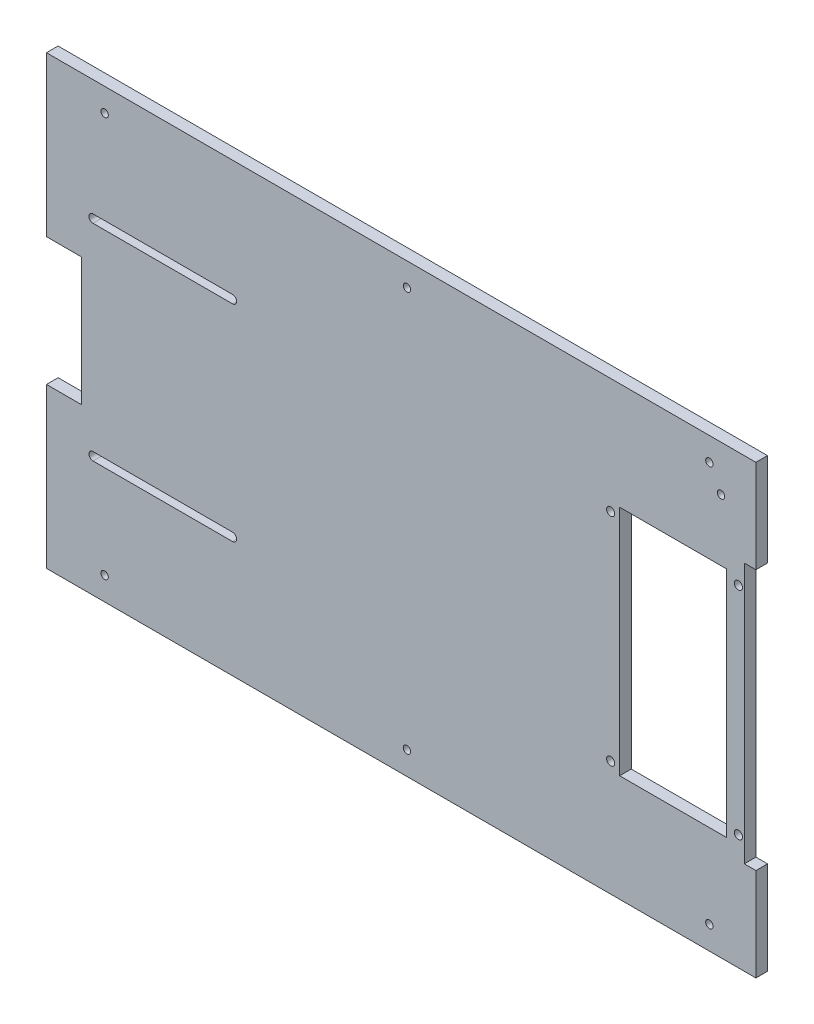
SolidWorks part; units mm, degrees
ref_plane "Front Plane" through (0, 0, 0) normal (0, 0, 1) x (1, 0, 0)
ref_plane "Top Plane" through (0, 0, 0) normal (0, 1, 0) x (1, 0, 0)
ref_plane "Right Plane" through (0, 0, 0) normal (1, 0, 0) x (0, 0, -1)
sketch "Sketch1" plane through (0, 0, 0) normal (0, 0, 1) x (1, 0, 0)
  line L1 (-150, 96) -> (150, 96)
  line L2 (-150, 96) -> (-150, -96)
  line L3 (-150, -96) -> (150, -96)
  line L4 (150, 96) -> (150, -96)
  line L5 (-150, 96) -> (150, -96) construction
  line L6 (-150, -96) -> (150, 96) construction
  point P0 (0, 0)
  dimension "D1" = 300
  dimension "D2" = 192
extrude "Boss-Extrude1" add sketch "Sketch1" along normal blind 5
sketch "Sketch2" plane through (0, 0, 0) normal (0, 0, -1) x (-1, 0, 0)
  circle A0 centre (-147.46, 46.46) radius 1.75
  circle A1 centre (-147.46, -46.46) radius 1.75
  circle A2 centre (-92.54, 46.46) radius 1.75
  circle A3 centre (-92.54, -46.46) radius 1.75
extrude "Cut-Extrude1" cut sketch "Sketch2" against normal through all
sketch "Sketch4" plane through (0, 0, 5) normal (0, 0, 1) x (1, 0, 0)
  line L1 (142.415, 50) -> (96.415, 50)
  line L2 (142.415, 50) -> (142.415, -50)
  line L3 (142.415, -50) -> (96.415, -50)
  line L4 (96.415, 50) -> (96.415, -50)
  line L5 (142.415, 50) -> (96.415, -50) construction
  line L6 (142.415, -50) -> (96.415, 50) construction
  point P0 (119.415, 0)
  point P5 (116.7278, 0)
  point P6 (77.5575, 0)
  point P7 (118.7424, 0)
  point P8 (119.0772, 0)
  point P9 (127.7432, -7.7776)
  point P10 (119.415, 0)
  dimension "D1" = 46
  dimension "D2" = 100
extrude "Cut-Extrude2" cut sketch "Sketch4" against normal through all
sketch "Sketch5" plane through (0, 0, 5) normal (0, 0, 1) x (1, 0, 0)
  line L0 (150, 96) -> (-150, 96) construction
  line L3 (-70, 44.25) -> (-130, 44.25) construction
  line L4 (-70, 42.5) -> (-130, 42.5)
  line L5 (-70, 46) -> (-130, 46)
  line L8 (-150, 96) -> (-150, -96) construction
  line L9 (-150, 0) -> (-49.2355, 0) construction
  line L10 (-70, -44.25) -> (-130, -44.25) construction
  line L11 (-70, -42.5) -> (-130, -42.5)
  line L12 (-70, -46) -> (-130, -46)
  line L14 (-135, 27.5) -> (-150, 27.5)
  line L15 (-135, 27.5) -> (-135, -27.5)
  line L16 (-135, -27.5) -> (-150, -27.5)
  line L17 (-150, 27.5) -> (-150, -27.5)
  arc A2 (-70, 42.5) -> (-70, 46) centre (-70, 44.25) ccw
  arc A3 (-130, 46) -> (-130, 42.5) centre (-130, 44.25) ccw
  arc A4 (-70, -42.5) -> (-70, -46) centre (-70, -44.25) cw
  arc A5 (-130, -46) -> (-130, -42.5) centre (-130, -44.25) cw
  point P7 (-100, 44.25)
  point P15 (-100, -44.25)
  point P25 (-135, 0)
  dimension "D1" = 1.75
  dimension "D2" = 50
  dimension "D3" = 20
  dimension "D4" = 60
  dimension "D5" = 55
  dimension "D6" = 15
extrude "Cut-Extrude3" cut sketch "Sketch5" against normal through all
sketch "Sketch6" plane through (0, 0, 0) normal (0, 0, -1) x (-1, 0, 0)
  line L0 (-150, 96) -> (150, 96) construction
  line L1 (-150, -96) -> (-150, 96) construction
  line L2 (-150, 0) -> (135, 0) construction
  line L3 (135, -27.5) -> (135, 27.5) construction
  circle A0 centre (-135, 86) radius 1.6
  circle A1 centre (-5, 86) radius 1.6
  circle A2 centre (125, 86) radius 1.6
  circle A3 centre (125, -86) radius 1.6
  circle A4 centre (-5, -86) radius 1.6
  circle A5 centre (-135, -86) radius 1.6
  dimension "D1" = 3.2
  dimension "D2" = 10
  dimension "D3" = 15
  dimension "D4" = 3
extrude "Cut-Extrude4" cut sketch "Sketch6" against normal through all
sketch "Sketch7" plane through (0, 0, 0) normal (0, 0, -1) x (-1, 0, 0)
  line L0 (-150, 0) -> (135, 0) construction
  line L1 (-150, 96) -> (-155, 96)
  line L2 (-150, 96) -> (-150, 56)
  line L3 (-150, 56) -> (-155, 56)
  line L4 (-155, 96) -> (-155, 56)
  line L5 (-150, -96) -> (-150, 96) construction
  line L6 (135, -27.5) -> (135, 27.5) construction
  line L7 (-155, -96) -> (-155, -56)
  line L8 (-150, -56) -> (-155, -56)
  line L9 (-150, -96) -> (-150, -56)
  line L10 (-150, -96) -> (-155, -96)
  dimension "D1" = 5
  dimension "D2" = 40
extrude "Boss-Extrude2" add sketch "Sketch7" against normal up to surface (5 mm away) up to face at (136.6, -86, 5)
sketch "Sketch8" plane through (0, 0, 0) normal (0, 0, -1) x (-1, 0, 0)
  circle A0 centre (-140, 76.5) radius 1.6
extrude "Cut-Extrude5" cut sketch "Sketch8" against normal through all
